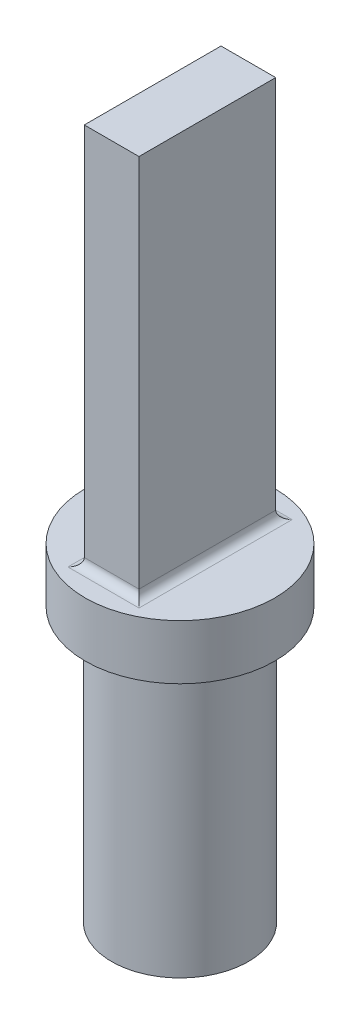
SolidWorks part; units mm, degrees
ref_plane "Front Plane" through (0, 0, 0) normal (0, 0, 1) x (1, 0, 0)
ref_plane "Top Plane" through (0, 0, 0) normal (0, 1, 0) x (1, 0, 0)
ref_plane "Right Plane" through (0, 0, 0) normal (1, 0, 0) x (0, 0, -1)
sketch "Sketch1" plane through (0, 0, 0) normal (0, 1, 0) x (1, 0, 0)
  circle A0 centre (0, 0) radius 17.325
  dimension "D1" = 34.65
extrude "Boss-Extrude1" add sketch "Sketch1" against normal blind 10
sketch "Sketch2" plane through (0, -10, 0) normal (0, -1, 0) x (1, 0, 0)
  circle A0 centre (0, 0) radius 12.5
  dimension "D1" = 25
extrude "Boss-Extrude2" add sketch "Sketch2" along normal blind 50
sketch "Sketch3" plane through (0, 0, 0) normal (0, 1, 0) x (1, 0, 0)
  line L0 (5, -12.5) -> (-5, 12.5) construction
  line L1 (5, -12.5) -> (-5, -12.5)
  line L2 (5, -12.5) -> (5, 12.5)
  line L3 (5, 12.5) -> (-5, 12.5)
  line L4 (-5, -12.5) -> (-5, 12.5)
  dimension "D1" = 10
  dimension "D2" = 25
extrude "Boss-Extrude3" add sketch "Sketch3" along normal blind 70
fillet "Fillet1" radius 1.5 4 edges at (0, 0, -12.5) (5, 0, 0) (0, 0, 12.5) (-5, 0, 0)
